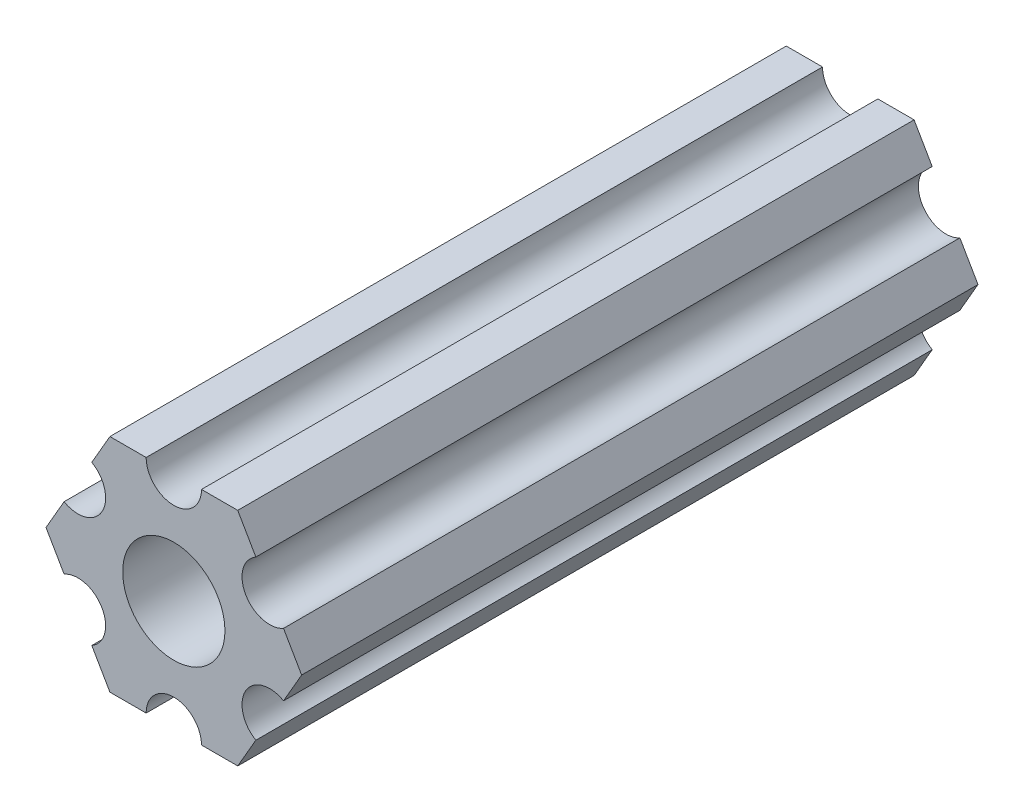
SolidWorks part; units mm, degrees
material "6061-T6 (SS)"
ref_plane "Alzado" through (0, 0, 0) normal (0, 0, 1) x (1, 0, 0)
ref_plane "Planta" through (0, 0, 0) normal (0, 1, 0) x (1, 0, 0)
ref_plane "Vista lateral" through (0, 0, 0) normal (1, 0, 0) x (0, 0, -1)
sketch "Croquis1" plane through (0, 0, 0) normal (0, 0, 1) x (1, 0, 0)
  line L24 (620.4484, 354.8104) -> (619.409, 356.6106)
  line L25 (619.409, 356.6106) -> (617.3304, 356.6106)
  line L26 (614.1554, 356.6106) -> (612.0767, 356.6106)
  line L27 (612.0767, 356.6106) -> (611.0374, 354.8104)
  line L28 (609.4499, 352.0608) -> (608.4105, 350.2606)
  line L29 (608.4105, 350.2606) -> (609.4499, 348.4604)
  line L30 (611.0374, 345.7108) -> (612.0767, 343.9106)
  line L31 (612.0767, 343.9106) -> (614.1554, 343.9106)
  line L32 (617.3304, 343.9106) -> (619.409, 343.9106)
  line L33 (619.409, 343.9106) -> (620.4484, 345.7108)
  line L34 (622.0359, 348.4604) -> (623.0752, 350.2606)
  line L35 (623.0752, 350.2606) -> (622.0359, 352.0608)
  arc A2 (614.276, 347.72) -> (617.2097, 352.8013) centre (615.7429, 350.2606) ccw
  arc A3 (617.2097, 352.8013) -> (614.276, 347.72) centre (615.7429, 350.2606) ccw
  arc A16 (614.9491, 355.2358) -> (617.3304, 356.6106) centre (615.7429, 356.6106) ccw
  arc A17 (614.1554, 356.6106) -> (614.9491, 355.2358) centre (615.7429, 356.6106) ccw
  arc A18 (609.4499, 352.0608) -> (611.0374, 354.8104) centre (610.2436, 353.4356) ccw
  arc A19 (611.0374, 345.7108) -> (609.4499, 348.4604) centre (610.2436, 347.0856) ccw
  arc A20 (617.3304, 343.9106) -> (614.1554, 343.9106) centre (615.7429, 343.9106) ccw
  arc A21 (622.0359, 348.4604) -> (620.4484, 345.7108) centre (621.2421, 347.0856) ccw
  arc A22 (620.4484, 352.0608) -> (622.0359, 352.0608) centre (621.2421, 353.4356) ccw
  arc A23 (620.4484, 354.8104) -> (620.4484, 352.0608) centre (621.2421, 353.4356) ccw
extrude "Saliente-Extruir1" add sketch "Croquis1" against normal blind 38.8
